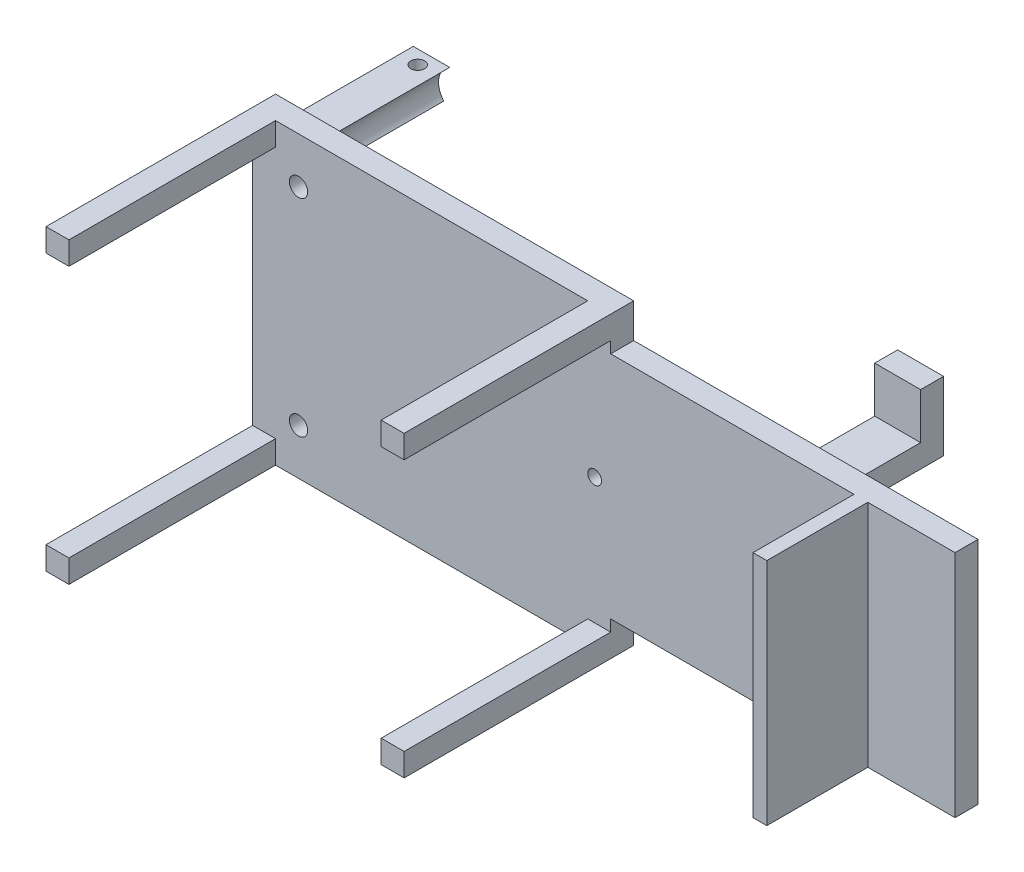
SolidWorks part; units mm, degrees
ref_plane "Alzado" through (0, 0, 0) normal (0, 0, 1) x (1, 0, 0)
ref_plane "Planta" through (0, 0, 0) normal (0, 1, 0) x (1, 0, 0)
ref_plane "Vista lateral" through (0, 0, 0) normal (1, 0, 0) x (0, 0, -1)
sketch "Croquis1" plane through (0, 0, 0) normal (0, 0, 1) x (1, 0, 0)
  line L1 (-76.5, -32.5) -> (1.5, -32.5)
  line L2 (-76.5, -32.5) -> (-76.5, 32.5)
  line L3 (-76.5, 32.5) -> (1.5, 32.5)
  line L4 (76.5, -25) -> (76.5, 25)
  line L5 (-76.5, 0) -> (127.0996, 0) construction
  line L6 (1.5, 32.5) -> (-3.5, 32.5)
  line L7 (-76.5, 27.5) -> (1.5, 27.5) construction
  line L8 (-76.5, -27.5) -> (1.5, -27.5) construction
  line L9 (-71.5, 0) -> (-61.5, 0) construction
  line L10 (1.5, -32.5) -> (1.5, 32.5)
  line L11 (-76.5, -32.5) -> (-71.5, -32.5)
  line L12 (1.5, -32.5) -> (-3.5, -32.5)
  line L13 (1.5, -32.5) -> (1.5, -27.5)
  line L14 (1.5, -27.5) -> (-3.5, -27.5)
  line L15 (76.5, 25) -> (1.5, 25)
  line L16 (76.5, -25) -> (1.5, -25)
  line L17 (-3.5, -32.5) -> (-3.5, -27.5)
  line L18 (-76.5, -32.5) -> (-76.5, -27.5)
  line L19 (-76.5, -27.5) -> (-71.5, -27.5)
  line L20 (-71.5, -32.5) -> (-71.5, -27.5)
  line L21 (-76.5, 32.5) -> (-71.5, 32.5)
  line L22 (-76.5, 32.5) -> (-76.5, 27.5)
  line L23 (-76.5, 27.5) -> (-71.5, 27.5)
  line L24 (-71.5, 32.5) -> (-71.5, 27.5)
  line L25 (1.5, 32.5) -> (1.5, 27.5)
  line L26 (1.5, 27.5) -> (-3.5, 27.5)
  line L27 (-3.5, 32.5) -> (-3.5, 27.5)
  circle A0 centre (-66.5, 22.5) radius 2
  circle A1 centre (-66.5, -22.5) radius 2
  circle A2 centre (-2, 0) radius 1.5
  point P0 (0, 0)
  point P12 (-41.5, 0)
  dimension "D5" = 78
  dimension "D10" = 4
  dimension "D11" = 4
  dimension "D12" = 5
  dimension "D13" = 65
  dimension "D15" = 3
  dimension "D16" = 3.5
  dimension "D1" = 45
  dimension "D2" = 5
  dimension "D3" = 5
  dimension "D4" = 55
  dimension "D6" = 50
  dimension "D7" = 5
  dimension "D8" = 10
  dimension "D9" = 10
  dimension "D14" = 5
  dimension "D17" = 50
  dimension "D18" = 75
  dimension "D19" = 153
  dimension "D20" = 7.5
  dimension "D21" = 5
  dimension "D22" = 78.5
extrude "Saliente-Extruir4" add sketch "Croquis1" along normal blind 5 contours L27 L3 L24 L23 L2 L19 L20 L1 L17 L14 L10 L26 A2 A0 A1 | L16 L4 L15 L10
sketch "Croquis3" plane through (0, 0, 0) normal (0, 0, -1) x (-1, 0, 0)
  line L0 (82.1817, 0) -> (-113.6683, 0) construction
  line L1 (-1.5, -27.5) -> (-1.5, -38.9029) construction
  line L2 (3.5, -32.5) -> (-4.0681, -32.5) construction
  line L3 (76.5, 32.5) -> (71.5, 32.5)
  line L4 (76.5, 32.5) -> (76.5, 27.5)
  line L5 (76.5, 27.5) -> (71.5, 27.5)
  line L6 (71.5, 32.5) -> (71.5, 27.5)
  line L7 (3.5, -32.5) -> (3.5, -27.5)
  line L8 (-1.5, -27.5) -> (3.5, -27.5)
  line L9 (3.5, 32.5) -> (-4.0681, 32.5) construction
  line L10 (-1.5, 27.5) -> (-1.5, 38.9029) construction
  line L11 (-1.5, -32.5) -> (-1.5, -27.5)
  line L12 (-1.5, 32.5) -> (3.5, 32.5)
  line L13 (-1.5, 32.5) -> (-1.5, 27.5)
  line L14 (-1.5, 27.5) -> (3.5, 27.5)
  line L15 (3.5, 32.5) -> (3.5, 27.5)
  line L16 (-1.5, -32.5) -> (3.5, -32.5)
  line L17 (71.5, -32.5) -> (71.5, -27.5)
  line L18 (76.5, -27.5) -> (71.5, -27.5)
  line L19 (76.5, -32.5) -> (76.5, -27.5)
  line L20 (76.5, -32.5) -> (71.5, -32.5)
extrude "Saliente-Extruir5" add sketch "Croquis3" against normal blind 50
sketch "Croquis4" plane through (0, 0, 5) normal (0, 0, 1) x (1, 0, 0)
  line L0 (76.5, -25) -> (76.5, 25) construction
  line L4 (76.5, -25) -> (1.5, -25) construction
  line L6 (57.5, 25) -> (54.5, 25)
  line L7 (57.5, 25) -> (57.5, -25)
  line L9 (57.5, -25) -> (54.5, -25)
  line L10 (54.5, 25) -> (54.5, -25)
  dimension "D1" = 3
  dimension "D2" = 50
  dimension "D3" = 19
extrude "Saliente-Extruir7" add sketch "Croquis4" along normal blind 22
sketch "Croquis6" plane through (0, 0, 0) normal (0, 0, -1) x (-1, 0, 0)
  line L0 (-1.5, 25) -> (-1.5, -25) construction
  line L1 (-1.5, 0) -> (-31.5, 0) construction
  line L2 (-31.5, 25) -> (-31.5, -25)
  line L3 (-76.5, 25) -> (-1.5, 25) construction
  line L4 (-76.5, -25) -> (-1.5, -25) construction
  line L5 (-41.5, 25) -> (-41.5, -25)
  line L6 (-76.5, 0) -> (10.0183, 0) construction
  line L7 (-76.5, -25) -> (-76.5, 25) construction
  line L8 (-41.5, -14.5) -> (-31.5, -14.5)
  line L9 (-41.5, 9.5) -> (-31.5, 9.5) construction
  line L10 (-41.5, -9.5) -> (-31.5, -9.5) construction
  line L11 (-41.5, 14.5) -> (-31.5, 14.5)
  line L12 (-41.5, 13.5) -> (-41.5, 9.5)
  line L13 (-31.5, 13.5) -> (-31.5, 9.5)
  line L14 (-31.5, -9.5) -> (-31.5, -13.5)
  line L15 (-41.5, -9.5) -> (-41.5, -13.5)
  line L17 (-41.5, 9.5) -> (-31.5, 9.5)
  line L18 (-41.5, 9.5) -> (-41.5, 13.5)
  line L20 (-31.5, 9.5) -> (-31.5, 13.5)
  line L22 (-41.5, -13.5) -> (-41.5, -9.5)
  line L23 (-41.5, -9.5) -> (-31.5, -9.5)
  line L24 (-31.5, -13.5) -> (-31.5, -9.5)
  point P24 (-51.481, 0)
  dimension "D1" = 10
  dimension "D2" = 30
  dimension "D3" = 5
  dimension "D4" = 10
  dimension "D5" = 19
  dimension "D6" = 5
extrude "Saliente-Extruir9" add sketch "Croquis6" along normal blind 27.5 contours L5 L17 L2 L11 | L23 L5 L8 L2
sketch "Croquis7" plane through (0, 14.5, 0) normal (0, 1, 0) x (1, 0, 0)
  line L0 (41.5, 27.5) -> (41.5, 0) construction
  line L1 (31.5, 27.5) -> (41.5, 27.5)
  line L2 (31.5, 27.5) -> (31.5, 22.5)
  line L3 (31.5, 22.5) -> (41.5, 22.5)
  line L4 (41.5, 27.5) -> (41.5, 22.5)
  dimension "D1" = 5
extrude "Saliente-Extruir10" add sketch "Croquis7" along normal blind 10
sketch "Croquis8" plane through (0, -14.5, 0) normal (0, -1, 0) x (1, 0, 0)
  line L0 (31.5, -27.5) -> (31.5, 0) construction
  line L1 (41.5, -27.5) -> (31.5, -27.5)
  line L2 (41.5, -27.5) -> (41.5, -22.5)
  line L3 (41.5, -22.5) -> (31.5, -22.5)
  line L4 (31.5, -27.5) -> (31.5, -22.5)
  dimension "D1" = 5
extrude "Saliente-Extruir11" add sketch "Croquis8" along normal blind 10
sketch "Croquis9" plane through (0, 0, 0) normal (0, 0, -1) x (-1, 0, 0)
  line L0 (-1.5, 0) -> (60.5, 0) construction
  line L1 (60.5, 32.5) -> (60.5, -32.5) construction
  line L2 (76.5, 32.5) -> (-1.5, 32.5) construction
  line L3 (76.5, -32.5) -> (-1.5, -32.5) construction
  line L4 (74.1097, 26.5) -> (74.1097, 19.5) construction
  line L5 (68.5, 22.5) -> (71, 22.5) construction
  line L6 (76.5, 26.5) -> (68.5616, 26.5) construction
  line L7 (69.8541, -19.5) -> (76.5, -19.5)
  line L8 (76.5, -32.5) -> (76.5, 32.5) construction
  line L9 (76.5, 19.5) -> (69.8541, 19.5) construction
  line L11 (76.5, -19.5) -> (69.8541, -19.5) construction
  line L12 (76.5, -26.5) -> (68.5616, -26.5) construction
  line L13 (68.5616, -26.5) -> (76.5, -26.5)
  line L14 (76.5, -26.5) -> (76.5, -19.5)
  line L15 (68.5616, 26.5) -> (76.5, 26.5)
  line L16 (76.5, 26.5) -> (76.5, 19.5)
  line L17 (76.5, 19.5) -> (69.8541, 19.5)
  circle A0 centre (66.5, 22.5) radius 2 construction
  arc A1 (69.8541, 19.5) -> (68.5616, 26.5) centre (66.5, 22.5) ccw
  arc A2 (69.8541, -19.5) -> (68.5616, -26.5) centre (66.5, -22.5) cw
extrude "Saliente-Extruir12" add sketch "Croquis9" along normal blind 30
sketch "Croquis10" plane through (0, 26.5, 0) normal (0, 1, 0) x (1, 0, 0)
  line L0 (-72.5308, 0) -> (-72.5308, 27) construction
  line L1 (-76.5, 0) -> (-68.5616, 0) construction
  circle A0 centre (-72.5308, 27) radius 1.5
extrude "Cortar-Extruir1" cut sketch "Croquis10" against normal blind 77
